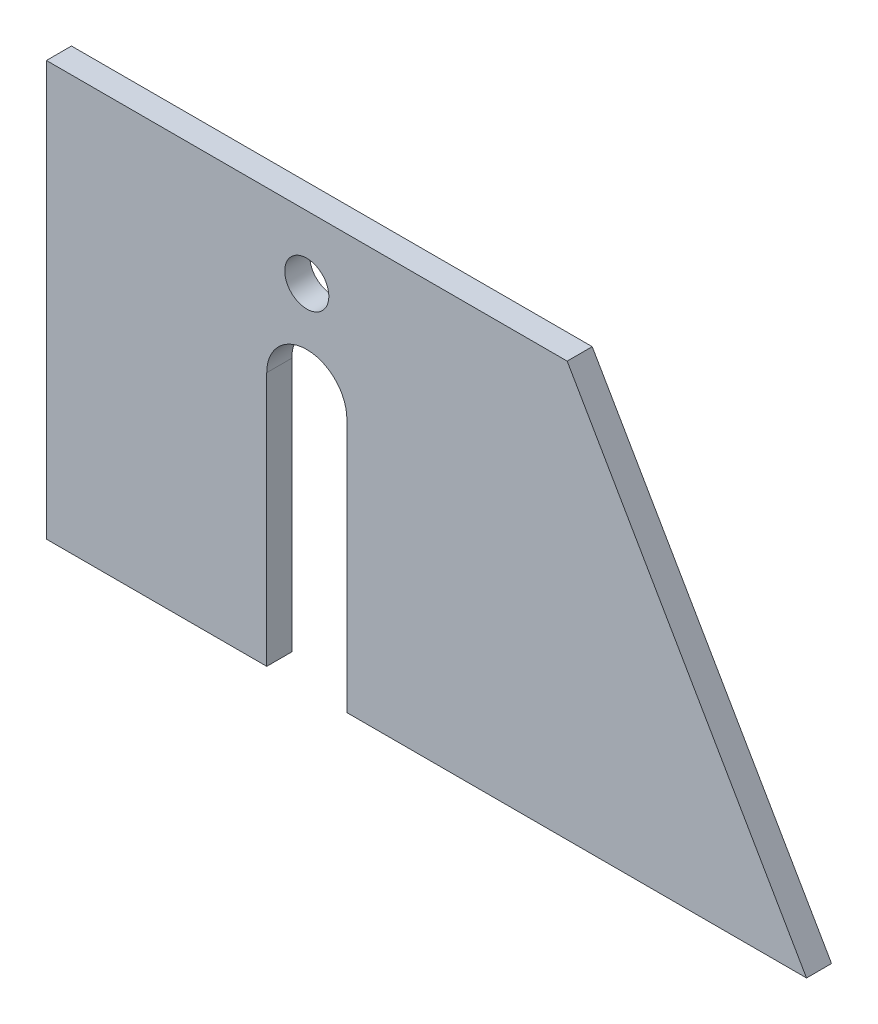
SolidWorks part; units mm, degrees
material "Plain Carbon Steel"
ref_plane "Front Plane" through (0, 0, 0) normal (0, 0, 1) x (1, 0, 0)
ref_plane "Top Plane" through (0, 0, 0) normal (0, 1, 0) x (1, 0, 0)
ref_plane "Right Plane" through (0, 0, 0) normal (1, 0, 0) x (0, 0, -1)
sketch "Sketch1" plane through (0, 0, 0) normal (0, 0, 1) x (1, 0, 0)
  line L1 (-32.5, 20) -> (32.5, 20)
  line L2 (-32.5, 20) -> (-32.5, -31.75)
  line L3 (-32.5, -31.75) -> (-5, -31.75)
  line L6 (5, -31.75) -> (32.5, -31.75)
  line L7 (-5, 0) -> (-5, -31.75)
  line L8 (5, 0) -> (5, -31.75)
  line L9 (32.5, 20) -> (62.3779, -31.75)
  line L10 (62.3779, -31.75) -> (32.5, -31.75)
  arc A0 (5, 0) -> (-5, 0) centre (0, 0) ccw
  circle A1 centre (0, 0) radius 5 construction
  circle A2 centre (0, 12.125) radius 2.75
  point P1 (0, 20)
  dimension "D1" = 10
  dimension "D5" = 5.5
  dimension "D2" = 65
  dimension "D3" = 20
  dimension "D4" = 31.75
  dimension "D6" = 12.125
  dimension "D7" = 120
extrude "Boss-Extrude1" add sketch "Sketch1" along normal blind 3.125
